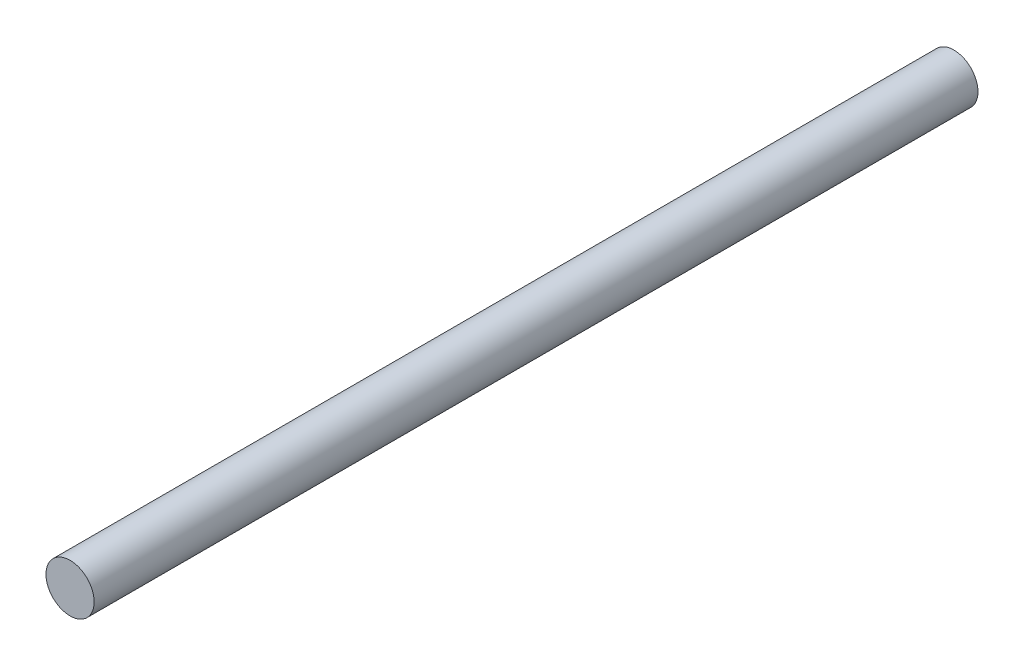
SolidWorks part; units mm, degrees
ref_plane "Front Plane" through (0, 0, 0) normal (0, 0, 1) x (1, 0, 0)
ref_plane "Top Plane" through (0, 0, 0) normal (0, 1, 0) x (1, 0, 0)
ref_plane "Right Plane" through (0, 0, 0) normal (1, 0, 0) x (0, 0, -1)
sketch "Sketch1" plane through (0, 0, 0) normal (0, 0, 1) x (1, 0, 0)
  circle A0 centre (0, 0) radius 1.5
  dimension "D1" = 3
extrude "Boss-Extrude2" add sketch "Sketch1" along normal blind 55
